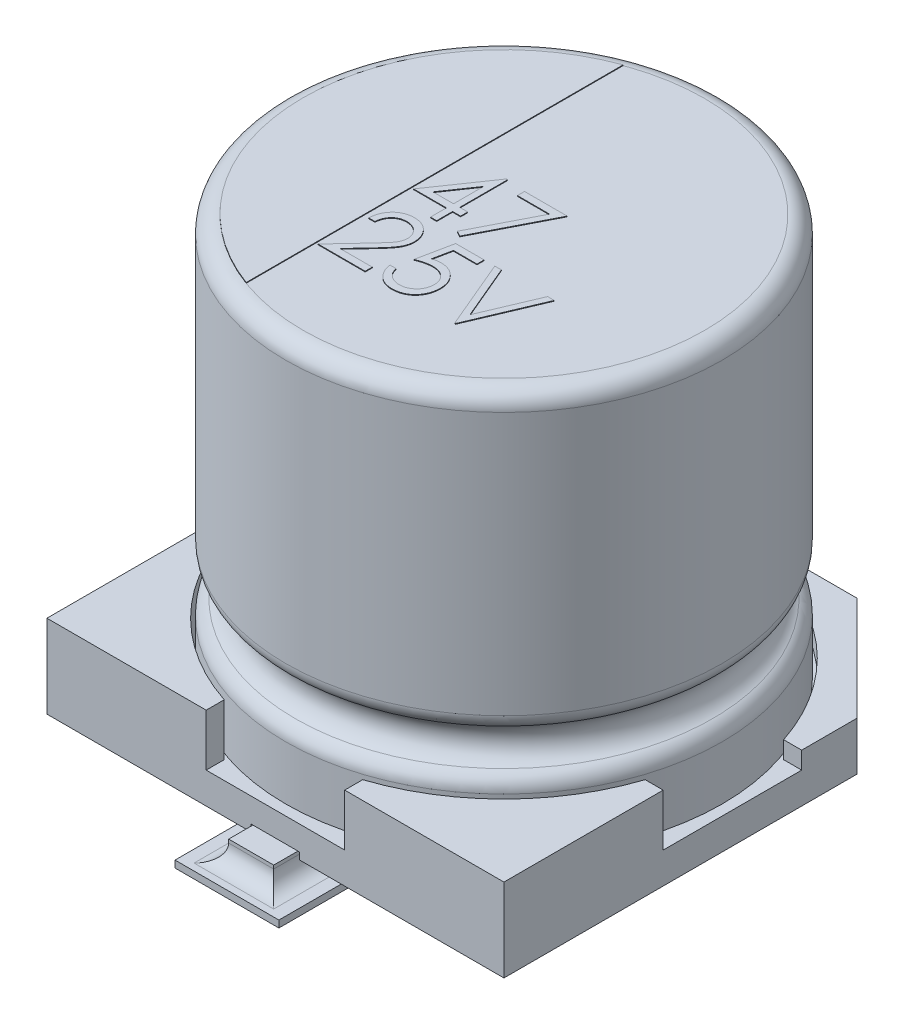
SolidWorks part; units mm, degrees
ref_plane "Front Plane" through (0, 0, 0) normal (0, 0, 1) x (1, 0, 0)
ref_plane "Top Plane" through (0, 0, 0) normal (0, 1, 0) x (1, 0, 0)
ref_plane "Right Plane" through (0, 0, 0) normal (1, 0, 0) x (0, 0, -1)
sketch "Sketch1" plane through (0, 0, 0) normal (0, 1, 0) x (1, 0, 0)
  line L1 (-3.3, 3.3) -> (3.3, 3.3)
  line L2 (-3.3, 3.3) -> (-3.3, -3.3)
  line L3 (-3.3, -3.3) -> (3.3, -3.3)
  line L4 (3.3, 3.3) -> (3.3, -3.3)
  line L5 (-3.3, 3.3) -> (3.3, -3.3) construction
  line L6 (-3.3, -3.3) -> (3.3, 3.3) construction
  point P0 (0, 0)
  dimension "D1" = 6.6
extrude "Boss-Extrude1" add sketch "Sketch1" along normal blind 1.2 from offset 0.3
sketch "Sketch2" plane through (0, 1.5, 0) normal (0, 1, 0) x (1, 0, 0)
  line L0 (3.3, -3.3) -> (3.3, 3.3) construction
  line L1 (-3.3, 1) -> (3.3, 1)
  line L2 (-3.3, 1) -> (-3.3, -1)
  line L3 (-3.3, -1) -> (3.3, -1)
  line L4 (3.3, 1) -> (3.3, -1)
  line L5 (-3.3, 1) -> (3.3, -1) construction
  line L6 (-3.3, -1) -> (3.3, 1) construction
  line L7 (-1, 3.3) -> (1, 3.3)
  line L8 (-1, 3.3) -> (-1, -3.3)
  line L9 (-1, -3.3) -> (1, -3.3)
  line L10 (1, 3.3) -> (1, -3.3)
  line L11 (-1, 3.3) -> (1, -3.3) construction
  line L12 (-1, -3.3) -> (1, 3.3) construction
  line L13 (3.3, 3.3) -> (-3.3, 3.3) construction
  circle A0 centre (0, 0) radius 3.2
  line M3 (3.3, -3.3) -> (3.3, 3.3)
  line M4 (3.3, 3.3) -> (-3.3, 3.3)
  line M5 (-3.3, 3.3) -> (-3.3, -3.3)
  line M6 (-3.3, -3.3) -> (3.3, -3.3)
  dimension "D1" = 6.4
  dimension "D2" = 2
  dimension "D4" = 2
extrude "Cut-Extrude1" cut sketch "Sketch2" against normal blind 0.75 contours L10 L1 L8 L3 | L8 A0 L10 L3 | L3 A0 L1 L10 | L10 A0 L8 L1 | L1 A0 L3 L8 | A0 L1 L3 M5 | A0 L10 L8 M4 | A0 L3 L1 M3 | A0 L8 L10 M6 | L3 A0 L8 | L8 A0 L1 | L1 A0 L10 | L10 A0 L3
sketch "Sketch3" plane through (0, 1.5, 0) normal (0, 1, 0) x (1, 0, 0)
  line L4 (-3.3, 3.3) -> (-3.3, 1)
  line L5 (-3.3, 1) -> (-3.0397, 1)
  line L6 (-1, 3.0397) -> (-1, 3.3)
  line L7 (-1, 3.3) -> (-3.3, 3.3)
  line L8 (-3.3, 3.3) -> (-3.3, 1)
  line L9 (-3.3, 1) -> (-3.0397, 1)
  line L10 (-1, 3.0397) -> (-1, 3.3)
  line L11 (-1, 3.3) -> (-3.3, 3.3)
  line L12 (3.3, 3.3) -> (1, 3.3)
  line L13 (1, 3.3) -> (1, 3.0397)
  line L14 (3.0397, 1) -> (3.3, 1)
  line L15 (3.3, 1) -> (3.3, 3.3)
  line L16 (3.3, 3.3) -> (1, 3.3)
  line L17 (1, 3.3) -> (1, 3.0397)
  line L18 (3.0397, 1) -> (3.3, 1)
  line L19 (3.3, 1) -> (3.3, 3.3)
  arc A1 (-1, 3.0397) -> (-3.0397, 1) centre (0, 0) ccw
  arc A2 (-1, 3.0397) -> (-3.0397, 1) centre (0, 0) ccw
  arc A3 (3.0397, 1) -> (1, 3.0397) centre (0, 0) ccw
  arc A4 (3.0397, 1) -> (1, 3.0397) centre (0, 0) ccw
  dimension "D1" = 0
  dimension "D2" = 0
extrude "Cut-Extrude2" cut sketch "Sketch3" against normal blind 0.5
chamfer "Chamfer1" distance 1.5 angle 45 2 edges at (-3.3, 0.65, -3.3) (3.3, 0.65, -3.3)
sketch "Sketch4" plane through (0, 0, 0) normal (1, 0, 0) x (0, 0, -1)
  line L0 (-1, 0.75) -> (1, 0.75) construction
  line L1 (-3.15, 0.75) -> (0, 0.75)
  line L2 (0, 0.75) -> (0, 6.55)
  line L3 (0, 6.55) -> (-2.9, 6.55)
  line L4 (-3.15, 6.3) -> (-3.15, 2.5071)
  line L5 (-3.15, 0.75) -> (-3.15, 1.5273)
  arc A0 (-3.15, 2.5071) -> (-3.0136, 2.2844) centre (-2.9, 2.5071) ccw
  arc A1 (-3.0136, 2.2844) -> (-3.0136, 1.75) centre (-3.15, 2.0172) cw
  arc A2 (-3.15, 1.5273) -> (-3.0136, 1.75) centre (-2.9, 1.5273) cw
  arc A3 (-3.15, 6.3) -> (-2.9, 6.55) centre (-2.9, 6.3) cw
  dimension "D1" = 0.3
  dimension "D5" = 0.25
  dimension "D2" = 5.8
  dimension "D3" = 3.15
  dimension "D4" = 1
revolve "Revolve1" add sketch "Sketch4" angle 360 about L2
sketch "Sketch5" plane through (0, 0.3, 0) normal (0, -1, 0) x (1, 0, 0)
  line L0 (-0.35, -3.3) -> (0.35, -3.3)
  line L4 (1.8, -3.3) -> (-1.8, -3.3) construction
  line L5 (-0.35, -3.3) -> (-0.4987, -1.2614)
  line L6 (0.35, -3.3) -> (0.4987, -1.2614)
  line L7 (0, 0) -> (-4.0015, 0) construction
  line L8 (-0.35, 3.3) -> (0.35, 3.3)
  line L9 (0.35, 3.3) -> (0.4987, 1.2614)
  line L10 (-0.35, 3.3) -> (-0.4987, 1.2614)
  arc A0 (-0.4987, -1.2614) -> (0.4987, -1.2614) centre (0, -1.225) cw
  arc A1 (-0.4987, 1.2614) -> (0.4987, 1.2614) centre (0, 1.225) ccw
  point P2 (0, -3.3)
  point P17 (0, 0)
  dimension "D2" = 0.5
  dimension "D1" = 0.7
  dimension "D3" = 1.225
extrude "Cut-Extrude3" cut sketch "Sketch5" against normal blind 0.1
sketch "Sketch6" plane through (0, 0.4, 0) normal (0, -1, 0) x (1, 0, 0)
  line L0 (0.35, 3.3) -> (3.3, 3.3) construction
  line L1 (-0.325, 3.65) -> (0.325, 3.65)
  line L2 (-0.325, 3.65) -> (-0.325, 1.225)
  line L3 (-0.325, 1.225) -> (0.325, 1.225) construction
  line L4 (0.325, 3.65) -> (0.325, 1.225)
  line L5 (-0.325, 3.65) -> (0.325, 1.225) construction
  line L6 (-0.325, 1.225) -> (0.325, 3.65) construction
  line L7 (0, 0) -> (-4.0015, 0) construction
  line L8 (0, 0) -> (-4.0015, 0) construction
  line L9 (0.325, -3.65) -> (0.325, -1.225)
  line L10 (-0.325, -3.65) -> (0.325, -3.65)
  line L11 (-0.325, -3.65) -> (-0.325, -1.225)
  arc A0 (-0.325, 1.225) -> (0.325, 1.225) centre (0, 1.225) ccw
  arc A1 (-0.325, -1.225) -> (0.325, -1.225) centre (0, -1.225) cw
  point P0 (0, 2.4375)
  dimension "D2" = 0.35
  dimension "D1" = 0.65
extrude "Boss-Extrude2" add sketch "Sketch6" along normal blind 0.4 separate body
sketch "Sketch7" plane through (0, 0.3, 0) normal (0, -1, 0) x (1, 0, 0)
  line L1 (-2, 2) -> (2, 2) construction
  line L2 (-2, 2) -> (-2, -2) construction
  line L3 (-2, -2) -> (2, -2) construction
  line L4 (2, 2) -> (2, -2) construction
  line L5 (-2, 2) -> (2, -2) construction
  line L6 (-2, -2) -> (2, 2) construction
  circle A0 centre (-2, 2) radius 0.5
  circle A1 centre (2, 2) radius 0.5
  circle A2 centre (2, -2) radius 0.5
  circle A3 centre (-2, -2) radius 0.5
  point P0 (0, 0)
  dimension "D2" = 1
  dimension "D3" = 1
  dimension "D4" = 1
  dimension "D5" = 1
  dimension "D1" = 4
extrude "Boss-Extrude3" add sketch "Sketch7" along normal blind 0.3
sketch "Sketch8" plane through (0, 0, 0) normal (0, -1, 0) x (1, 0, 0)
  line L0 (0, 0) -> (-3.3, 0) construction
  line L1 (-0.75, -4) -> (0.75, -4)
  line L2 (-0.75, -4) -> (-0.75, -2)
  line L3 (-0.75, -2) -> (0.75, -2)
  line L4 (0.75, -4) -> (0.75, -2)
  line L5 (-0.75, -4) -> (0.75, -2) construction
  line L6 (-0.75, -2) -> (0.75, -4) construction
  line L7 (-3.3, -1.8) -> (-3.3, 3.3) construction
  line L8 (0.75, 4) -> (0.75, 2)
  line L9 (-0.75, 2) -> (0.75, 2)
  line L10 (-0.75, 4) -> (-0.75, 2)
  line L11 (-0.75, 4) -> (0.75, 4)
  point P0 (0, -3)
  dimension "D1" = 1.5
  dimension "D2" = 2
  dimension "D3" = 4
extrude "Boss-Extrude4" add sketch "Sketch8" against normal blind 0.1
fillet "Fillet1" radius 0.25 3 edges at (-0.325, 0.1, 2.825) (0, 0.1, 3.65) (0.325, 0.1, 2.825)
fillet "Fillet2" radius 0.25 3 edges at (-0.325, 0.1, -2.825) (0, 0.1, -3.65) (0.325, 0.1, -2.825)
sketch "Sketch9" plane through (0, 6.55, 0) normal (0, 1, 0) x (1, 0, 0)
  line L0 (-1, -2.7221) -> (-1, -1.7221)
  line L1 (-1, -1.7221) -> (-1, -0.574)
  line L2 (-1, -0.574) -> (-1, 0.574)
  line L3 (-1, 0.574) -> (-1, 1.7221)
  line L4 (-1, 1.7221) -> (-1, 2.7221)
  line L5 (-1, -1.7221) -> (2.3333, -1.7221) construction
  line L6 (-1, -0.574) -> (2.8426, -0.574) construction
  line L7 (-1, 0.574) -> (2.8426, 0.574) construction
  circle A4 centre (0, 0) radius 2.9 construction
  circle A5 centre (0, 0) radius 2.9 construction
  arc A6 (-1, -2.7221) -> (-1, 2.7221) centre (0, 0) cw
  text T0 "47" font "Century Gothic" height 1
  text T1 "25V" font "Century Gothic" height 1
  dimension "D1" = 1
  dimension "D2" = 1
extrude "Boss-Extrude5" add sketch "Sketch9" along normal blind 0.01 separate body
